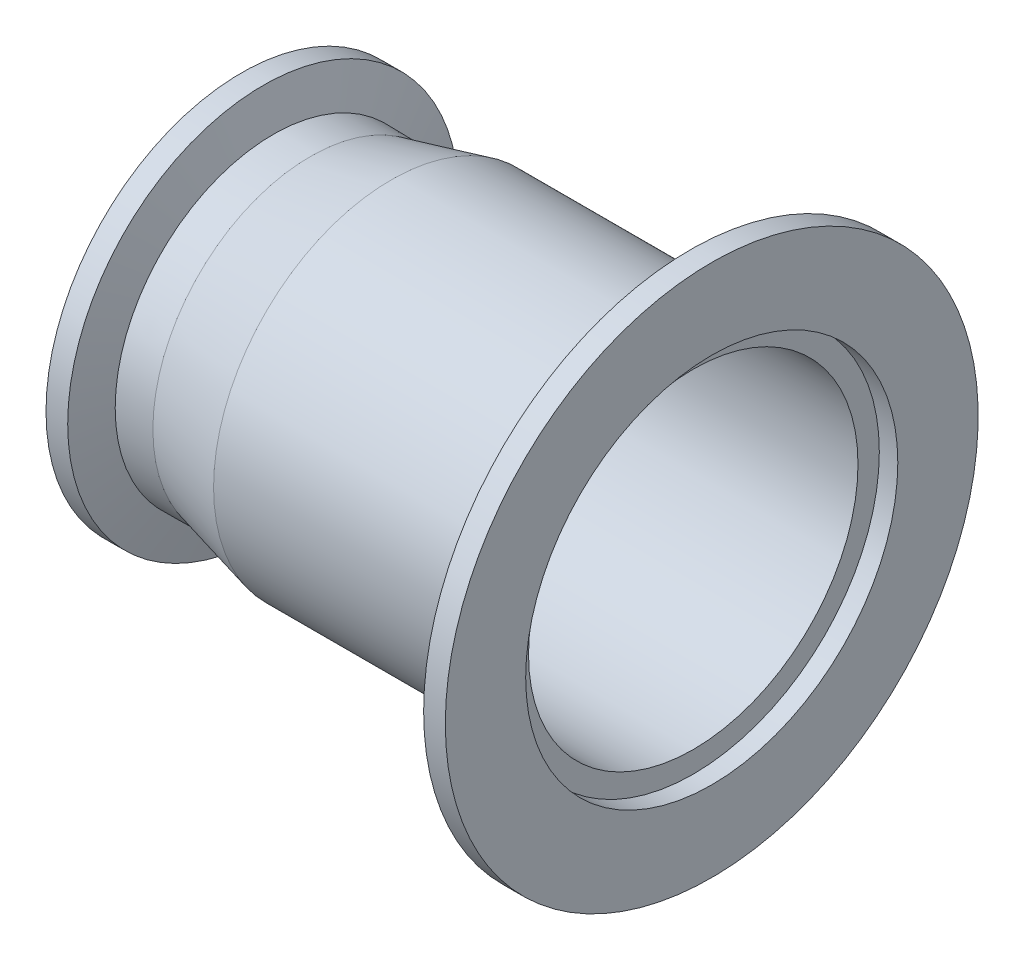
SolidWorks part; units mm, degrees
ref_plane "Front Plane" through (0, 0, 0) normal (0, 0, 1) x (1, 0, 0)
ref_plane "Top Plane" through (0, 0, 0) normal (0, 1, 0) x (1, 0, 0)
ref_plane "Right Plane" through (0, 0, 0) normal (1, 0, 0) x (0, 0, -1)
sketch "Sketch1" plane through (0, 0, 0) normal (0, 1, 0) x (1, 0, 0)
  line L0 (3.0624, 12.797) -> (6.1124, 12.797)
  line L1 (6.1124, 12.797) -> (7.5224, 7.527)
  line L2 (7.5224, 7.527) -> (12.7624, 7.467)
  line L3 (12.7624, 7.467) -> (24.1051, 10.277)
  line L4 (24.1051, 10.277) -> (64.1051, 10.277)
  line L5 (3.0624, 12.797) -> (3.0624, 5.897)
  line L6 (3.0624, 5.897) -> (5.6624, 5.897)
  line L7 (5.6624, 5.897) -> (5.6624, 2.897)
  line L8 (5.6624, 2.897) -> (28.146, 8.467)
  line L9 (28.146, 8.467) -> (66.5851, 8.467)
  line L10 (5.6624, 2.897) -> (5.6624, -14.698)
  line L12 (64.1051, 10.277) -> (64.1051, 15.187)
  line L13 (64.1051, 15.187) -> (66.1351, 22.767)
  line L14 (66.1351, 22.767) -> (69.1851, 22.767)
  line L15 (69.1851, 22.767) -> (69.1851, 11.467)
  line L16 (69.1851, 11.467) -> (66.5851, 11.467)
  line L17 (66.5851, 11.467) -> (66.5851, 8.467)
  line L18 (0, -14.698) -> (60.4818, -14.698)
revolve "Revolve3" add sketch "Sketch1" angle 360 about L18
